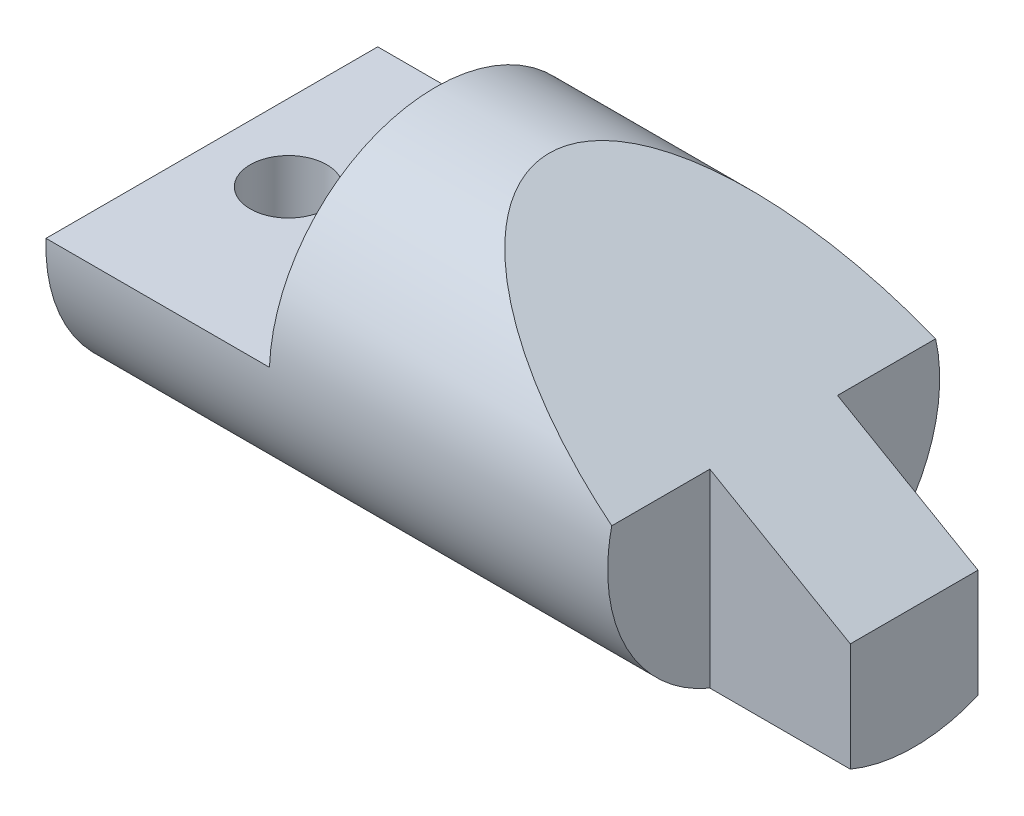
SolidWorks part; units mm, degrees
ref_plane "Front Plane" through (0, 0, 0) normal (0, 0, 1) x (1, 0, 0)
ref_plane "Top Plane" through (0, 0, 0) normal (0, 1, 0) x (1, 0, 0)
ref_plane "Right Plane" through (0, 0, 0) normal (1, 0, 0) x (0, 0, -1)
sketch "Sketch2" plane through (0, 0, 0) normal (1, 0, 0) x (0, 0, -1)
  circle A0 centre (0, 0) radius 26
  point P2 (0, 0)
  dimension "D1" = 52
extrude "Boss-Extrude1" add sketch "Sketch2" along normal blind 110
sketch "Sketch3" plane through (0, 0, 0) normal (0, 0, 1) x (1, 0, 0)
  line L0 (0, 1) -> (35, 1)
  line L1 (0, 26) -> (0, -26) construction
  line L2 (35, 1) -> (35, 26)
  line L3 (110, 26) -> (0, 26) construction
  line L4 (35, 26) -> (0, 26)
  line L5 (0, 26) -> (0, 1)
  line L6 (52.8423, 26) -> (110, -7)
  line L7 (110, -26) -> (110, 26) construction
  line L8 (52.8423, 26) -> (110, 26)
  line L9 (110, 26) -> (110, -7)
  dimension "D1" = 25
  dimension "D2" = 35
  dimension "D3" = 8
  dimension "D4" = 30
extrude "Cut-Extrude1" cut sketch "Sketch3" against normal up to next and the other way up to next
sketch "Sketch4" plane through (0, 1, 0) normal (0, 1, 0) x (1, 0, 0)
  line L0 (35, 25.9808) -> (0, 25.9808) construction
  line L1 (0, -25.9808) -> (0, 25.9808) construction
  circle A0 centre (12, 0) radius 6
  point P2 (0, 0)
  point P6 (17.5, 25.9808)
  point P7 (0, 0)
  dimension "D1" = 12
  dimension "D2" = 12
extrude "Cut-Extrude2" cut sketch "Sketch4" against normal up to next
sketch "Sketch6" plane through (0, 0, 0) normal (0, 1, 0) x (1, 0, 0)
  line L0 (88, 26) -> (88, 10)
  line L1 (97.8756, 26) -> (0, 26) construction
  line L2 (88, 10) -> (110, 10)
  line L3 (110, -25.04) -> (110, 25.04) construction
  line L4 (88, -26) -> (110, -26)
  line L7 (88, 26) -> (110, 26)
  line L8 (110, 26) -> (110, 10)
  line L11 (110, -26) -> (110, -10)
  line L12 (110, -10) -> (88, -10)
  line L13 (88, -10) -> (88, -26)
  point P12 (0, 0)
  point P13 (110, 0)
  point P15 (111.4058, -25.9808)
  point P16 (110, -26)
  dimension "D1" = 22
  dimension "D2" = 26
  dimension "D3" = 16
extrude "Cut-Extrude4" cut sketch "Sketch6" against normal up to next (0.6491 mm away) and the other way up to next
